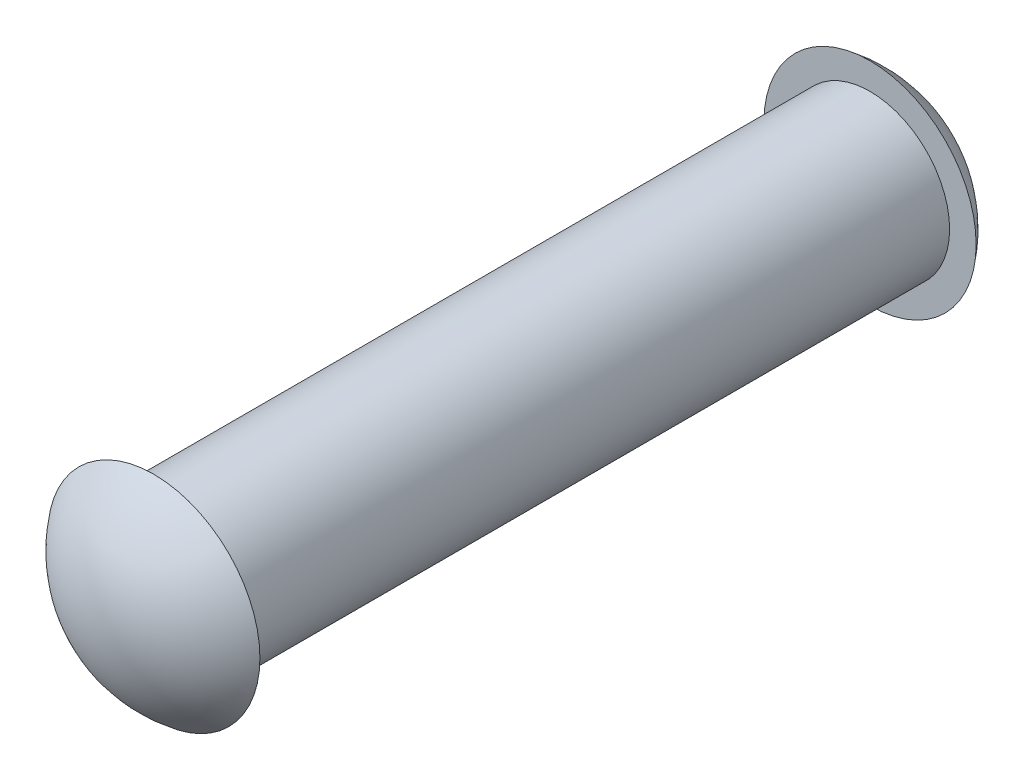
SolidWorks part; units mm, degrees
ref_plane "Alzado" through (0, 0, 0) normal (0, 0, 1) x (1, 0, 0)
ref_plane "Planta" through (0, 0, 0) normal (0, 1, 0) x (1, 0, 0)
ref_plane "Vista lateral" through (0, 0, 0) normal (1, 0, 0) x (0, 0, -1)
sketch "Croquis1" plane through (0, 0, 0) normal (0, 0, 1) x (1, 0, 0)
  circle A0 centre (-23.1699, 0) radius 3
  circle A2 centre (-23.1699, 0) radius 3 construction
extrude "Saliente-Extruir1" add sketch "Croquis1" against normal up to surface (27 mm away)
ref_plane "Plano1" through (0, 0, -13.5) normal (0, 0, 1) x (1, 0, 0)
sketch "Croquis2" plane through (0, 0, 0) normal (0, 1, 0) x (1, 0, 0)
  line L0 (-23.1699, 0) -> (-23.1699, -2)
  line L1 (-26.1699, 0) -> (-20.1699, 0) construction
  line L2 (-5.6269, 0) -> (-23.1699, 0) construction
  line L3 (-19.1699, 0) -> (-23.1699, 0)
  arc A0 (-23.1699, -2) -> (-19.1699, 0) centre (-23.1699, 3) ccw
  dimension "D1" = 2
  dimension "D2" = 4
revolve "Revolución1" add sketch "Croquis2" angle 360 about L0
mirror "Simetría1" about plane through (0, 0, -13.5) normal (0, 0, 1) of "Revolución1"
